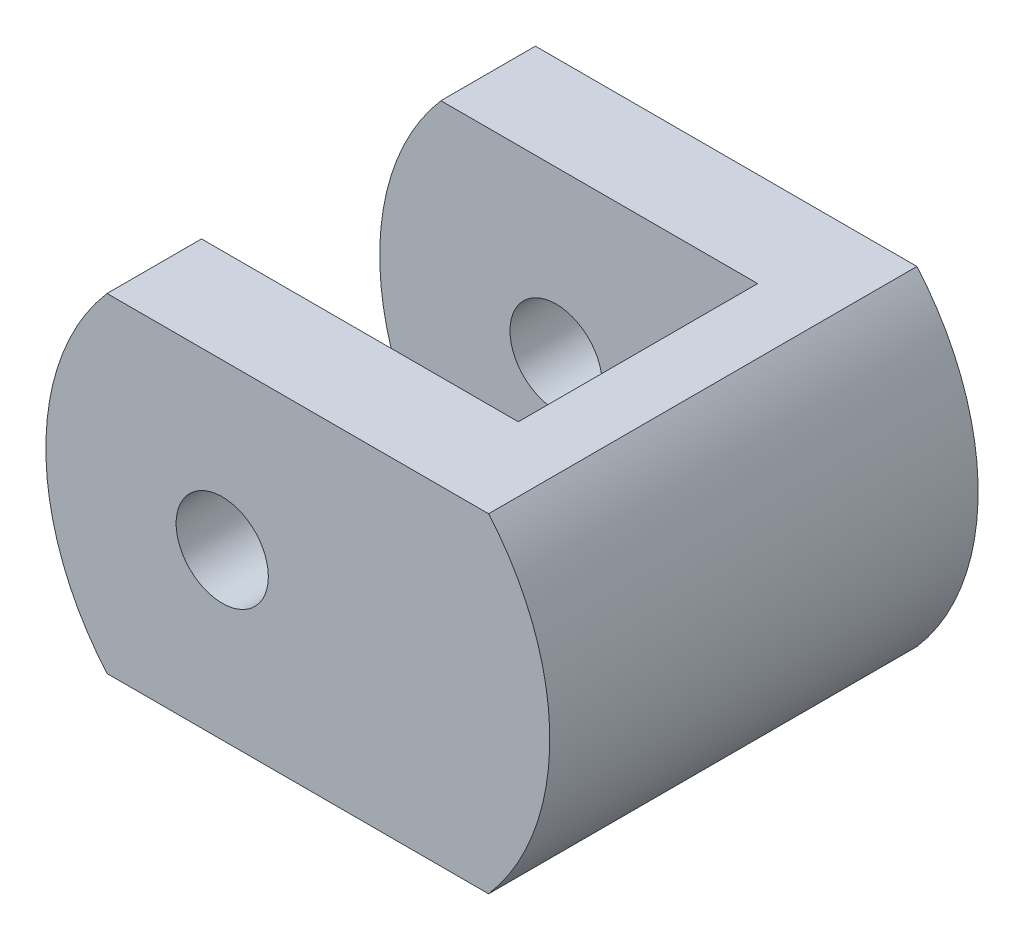
SolidWorks part; units mm, degrees
ref_plane "Front Plane" through (0, 0, 0) normal (0, 0, 1) x (1, 0, 0)
ref_plane "Top Plane" through (0, 0, 0) normal (0, 1, 0) x (1, 0, 0)
ref_plane "Right Plane" through (0, 0, 0) normal (1, 0, 0) x (0, 0, -1)
sketch "Sketch1" plane through (0, 0, 0) normal (0, 1, 0) x (1, 0, 0)
  line L0 (-3.81, 4.445) -> (3.81, 4.445) construction
  line L1 (3.81, 4.445) -> (3.81, -4.445) construction
  line L2 (3.81, -4.445) -> (-3.81, -4.445) construction
  line L3 (-3.81, -4.445) -> (-3.81, 4.445) construction
  line L4 (-3.81, 4.445) -> (3.81, -4.445) construction
  line L5 (0, 0) -> (0, 9.2822) construction
  line L7 (0, -10.795) -> (12.7, -10.795)
  line L8 (0, -10.795) -> (0, 10.795)
  line L9 (0, 10.795) -> (12.7, 10.795)
  line L10 (12.7, -10.795) -> (12.7, 10.795)
  point P4 (0, 0)
  dimension "D1" = 7.62
  dimension "D2" = 8.89
  dimension "D3" = 6.35
  dimension "D4" = 6.35
  dimension "D5" = 12.7
revolve "Revolve1" add sketch "Sketch1" angle 360 about L8
sketch "Sketch3" plane through (0, 0, 0) normal (0, 1, 0) x (1, 0, 0)
  line L0 (-12.7, 10.795) -> (-12.7, -10.795) construction
  line L1 (-12.7, -6.0325) -> (6.35, -6.0325)
  line L2 (-12.7, -6.0325) -> (-12.7, 6.0325)
  line L3 (-12.7, 6.0325) -> (6.35, 6.0325)
  line L4 (6.35, -6.0325) -> (6.35, 6.0325)
  line L5 (3.81, 4.445) -> (3.81, -4.445) construction
  line L6 (12.7, 10.795) -> (-12.7, 10.795) construction
  line L7 (-12.7, -10.795) -> (12.7, -10.795) construction
  dimension "D1" = 2.54
  dimension "D2" = 4.7625
  dimension "D3" = 4.7625
extrude "Cut-Extrude1" cut sketch "Sketch3" against normal through all both and the other way through all
sketch "Sketch4" plane through (0, 0, 0) normal (0, 0, 1) x (1, 0, 0)
  line L0 (-9.6158, 8.2962) -> (9.6158, 8.2962)
  line L1 (-9.6158, -8.2962) -> (9.6158, -8.2962)
  line L2 (-9.6158, -8.2962) -> (-9.6158, -13.6142)
  line L3 (-9.6158, -13.6142) -> (9.6158, -13.6142)
  line L4 (9.6158, -13.6142) -> (9.6158, -8.2962)
  line L5 (9.6158, 8.2962) -> (9.6158, 14.1164)
  line L6 (9.6158, 14.1164) -> (-9.6158, 13.9397)
  line L7 (-9.6158, 13.9397) -> (-9.6158, 8.2962)
  circle A0 centre (0, 0) radius 12.7 construction
  point P6 (-9.0052, 8.7925)
extrude "Cut-Extrude2" cut sketch "Sketch4" against normal through all both and the other way through all
sketch "Sketch5" plane through (0, 0, 10.795) normal (0, 0, 1) x (1, 0, 0)
  line L1 (-3.81, 0) -> (3.81, 0) construction
  line L2 (-3.81, 0) -> (3.81, 0) construction
  circle A0 centre (-3.81, 0) radius 2.3241
  point P2 (-3.81, 0)
  dimension "D1" = 4.6482
extrude "Cut-Extrude3" cut sketch "Sketch5" against normal through all both and the other way through all
